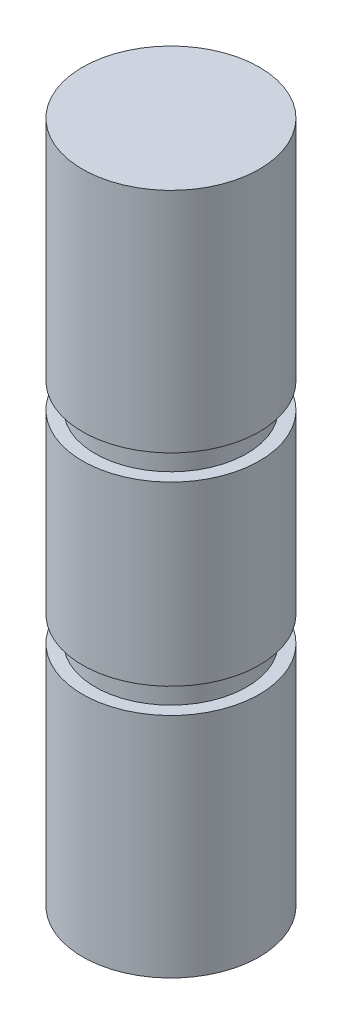
SolidWorks part; units mm, degrees
material "普通碳钢"
ref_plane "前视基准面" through (0, 0, 0) normal (0, 0, 1) x (1, 0, 0)
ref_plane "上视基准面" through (0, 0, 0) normal (0, 1, 0) x (1, 0, 0)
ref_plane "右视基准面" through (0, 0, 0) normal (1, 0, 0) x (0, 0, -1)
sketch "草图1" plane through (0, 0, 0) normal (1, 0, 0) x (0, 0, -1)
  line L0 (0, -13.5) -> (0, 21.2269) construction
  line L1 (0, 13.5) -> (3.5, 13.5)
  line L2 (3.5, 13.5) -> (3.5, 4.5)
  line L3 (3.5, 4.5) -> (3, 4.5)
  line L4 (3.5, 3.5) -> (3.5, -3.5)
  line L5 (3.5, -3.5) -> (3, -3.5)
  line L6 (3, -3.5) -> (3, -4.5)
  line L7 (3, -4.5) -> (3.5, -4.5)
  line L8 (3.5, -4.5) -> (3.5, -13.5)
  line L9 (3.5, -13.5) -> (0, -13.5)
  line L10 (0, -13.5) -> (0, 13.5)
  line L11 (3, 4.5) -> (3, 3.5)
  line L12 (3, 3.5) -> (3.5, 3.5)
  dimension "D1" = 3.5
  dimension "D2" = 7
  dimension "D3" = 1
  dimension "D4" = 1
  dimension "D5" = 0.5
  dimension "D6" = 9
  dimension "D7" = 9
revolve "旋转1" add sketch "草图1" angle 360 about L0
